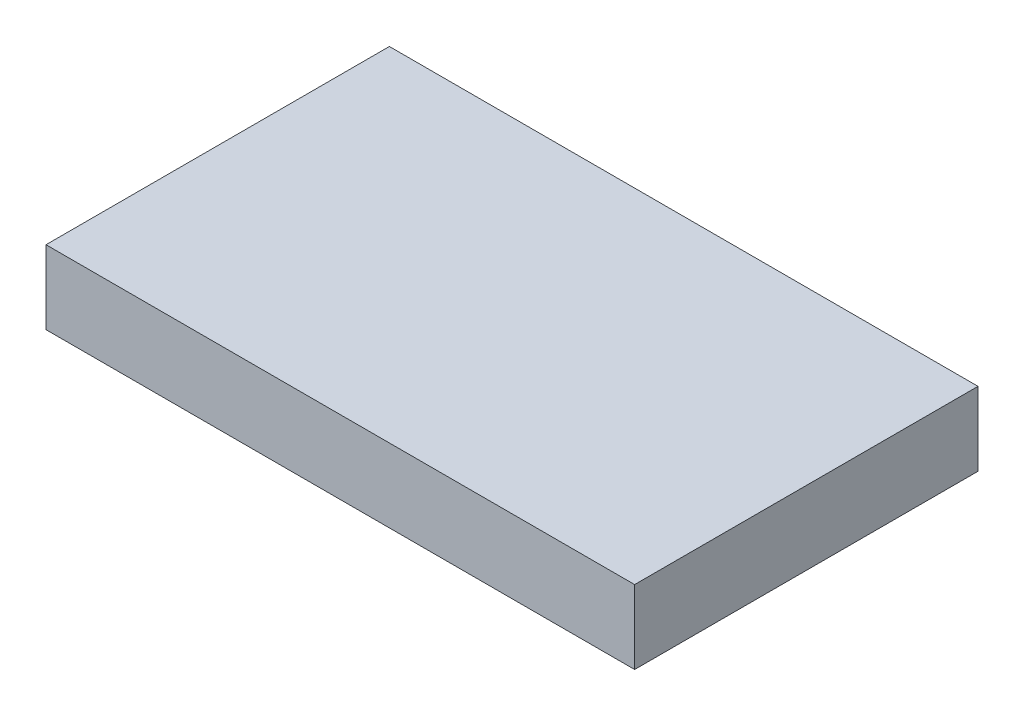
SolidWorks part; units mm, degrees
ref_plane "Front Plane" through (0, 0, 0) normal (0, 0, 1) x (1, 0, 0)
ref_plane "Top Plane" through (0, 0, 0) normal (0, 1, 0) x (1, 0, 0)
ref_plane "Right Plane" through (0, 0, 0) normal (1, 0, 0) x (0, 0, -1)
sketch "Sketch1" plane through (0, 0, 0) normal (0, 1, 0) x (1, 0, 0)
  line L1 (-29.0806, 17.8492) -> (31.8794, 17.8492)
  line L2 (-29.0806, 17.8492) -> (-29.0806, -17.7108)
  line L3 (-29.0806, -17.7108) -> (31.8794, -17.7108)
  line L4 (31.8794, 17.8492) -> (31.8794, -17.7108)
  dimension "D1" = 60.96
  dimension "D2" = 35.56
extrude "Boss-Extrude1" add sketch "Sketch1" along normal blind 7.62
